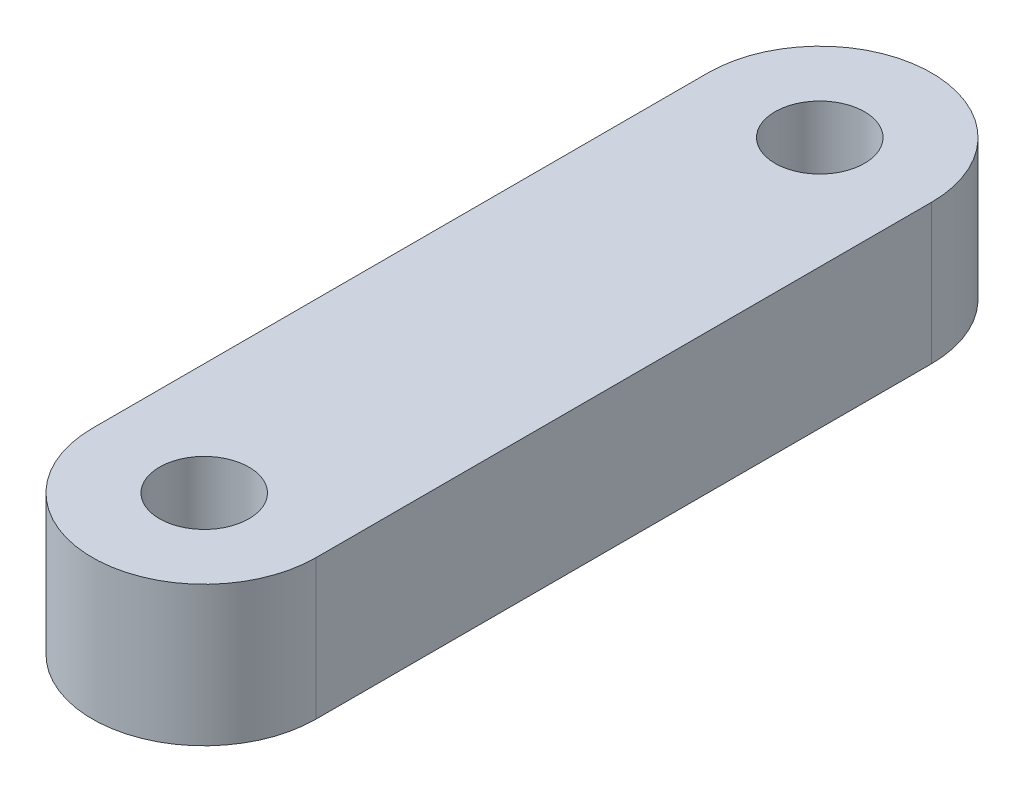
SolidWorks part; units mm, degrees
ref_plane "前视基准面" through (0, 0, 0) normal (0, 0, 1) x (1, 0, 0)
ref_plane "上视基准面" through (0, 0, 0) normal (0, 1, 0) x (1, 0, 0)
ref_plane "右视基准面" through (0, 0, 0) normal (1, 0, 0) x (0, 0, -1)
sketch "草图1" plane through (0, 0, 0) normal (0, 1, 0) x (1, 0, 0)
  line L0 (0, -11) -> (0, 11) construction
  line L1 (-4, -11) -> (-4, 11)
  line L2 (4, -11) -> (4, 11)
  arc A0 (-4, -11) -> (4, -11) centre (0, -11) ccw
  arc A1 (4, 11) -> (-4, 11) centre (0, 11) ccw
  circle A2 centre (0, 11) radius 1.6
  circle A3 centre (0, -11) radius 1.6
  point P2 (0, 0)
  dimension "D2" = 3.2
  dimension "D3" = 4
  dimension "D1" = 22
extrude "凸台-拉伸1" add sketch "草图1" along normal blind 5
